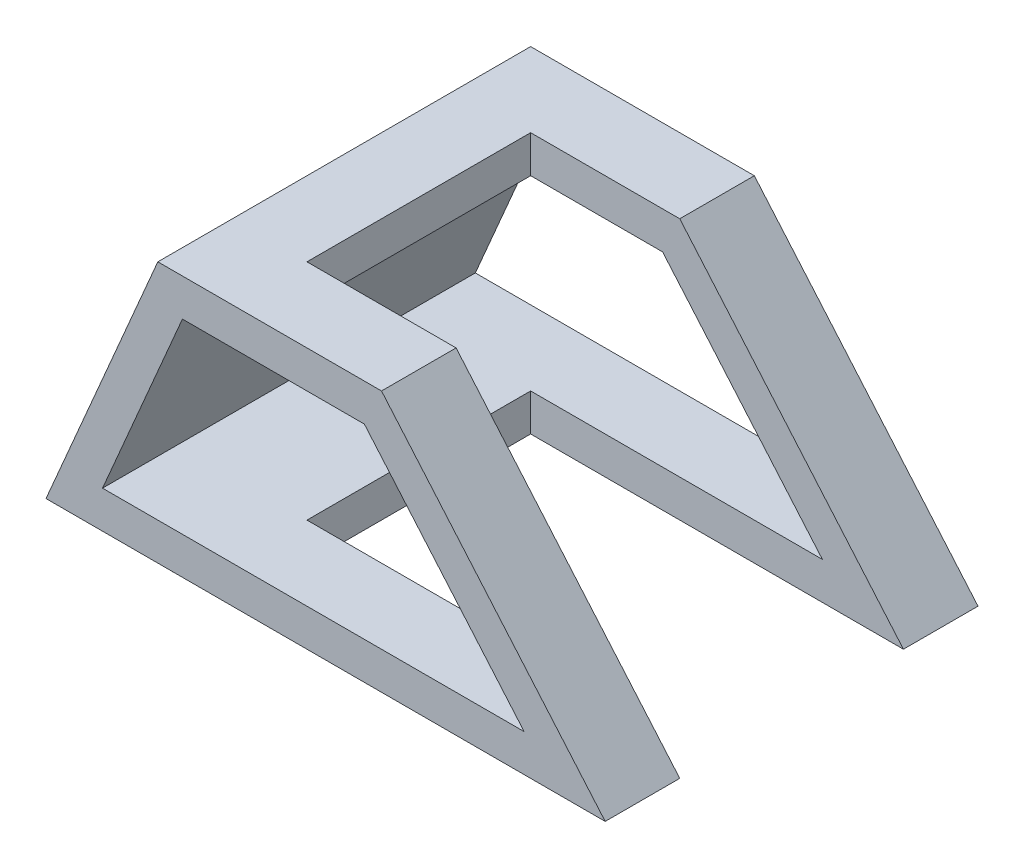
SolidWorks part; units mm, degrees
material "AISI 1020"
ref_plane "Front Plane" through (0, 0, 0) normal (0, 0, 1) x (1, 0, 0)
ref_plane "Top Plane" through (0, 0, 0) normal (0, 1, 0) x (1, 0, 0)
ref_plane "Right Plane" through (0, 0, 0) normal (1, 0, 0) x (0, 0, -1)
sketch "Esquisse1" plane through (0, 0, 0) normal (0, 0, 1) x (1, 0, 0)
  line L0 (0, 0) -> (164.5973, 0) construction
  line L5 (0, 0) -> (150, 0)
  line L6 (150, 0) -> (90, 70)
  line L7 (90, 70) -> (30, 70)
  line L8 (30, 70) -> (0, 0)
  line L9 (36.594, 60) -> (15.1654, 10)
  line L10 (15.1654, 10) -> (128.2578, 10)
  line L11 (128.2578, 10) -> (85.4007, 60)
  line L12 (85.4007, 60) -> (36.594, 60)
  dimension "D1" = 150
  dimension "D2" = 70
  dimension "D3" = 60
  dimension "D4" = 60
  dimension "D5" = 10
extrude "Boss.-Extru.1" add sketch "Esquisse1" against normal blind 100
sketch "Esquisse5" plane through (0, 0, 0) normal (0, -1, 0) x (1, 0, 0)
  line L0 (150, -100) -> (150, 0) construction
  line L1 (150, -20) -> (50, -20)
  line L2 (150, -20) -> (150, -80)
  line L3 (150, -80) -> (50, -80)
  line L4 (50, -20) -> (50, -80)
  line L5 (0, 0) -> (150, 0) construction
  line L6 (0, -100) -> (150, -100) construction
  point P6 (100, -20)
  dimension "D1" = 100
  dimension "D2" = 20
  dimension "D3" = 20
  dimension "D4" = 60
extrude "Enlèv. mat.-Extru.2" cut sketch "Esquisse5" against normal blind 10
sketch "Esquisse6" plane through (86.4706, 74.1176, 0) normal (0.7593, 0.6508, 0) x (0, 0, -1)
  line L0 (80, -84.4479) -> (20, -84.4479) construction
  line L1 (80, -84.4479) -> (20, -84.4479)
  line L2 (80, -84.4479) -> (80, -5.4233)
  line L3 (80, -5.4233) -> (20, -5.4233)
  line L4 (20, -84.4479) -> (20, -5.4233)
  line L5 (100, -5.4233) -> (0, -5.4233) construction
  line L6 (100, -97.6187) -> (100, -5.4233) construction
  line L7 (0, -97.6187) -> (0, -5.4233) construction
  point P8 (80, -44.9356)
  dimension "D1" = 60
  dimension "D2" = 20
  dimension "D3" = 20
extrude "Enlèv. mat.-Extru.3" cut sketch "Esquisse6" against normal blind 10
sketch "Esquisse7" plane through (0, 70, 0) normal (0, 1, 0) x (1, 0, 0)
  line L1 (90, 80) -> (50, 80)
  line L2 (90, 80) -> (90, 20)
  line L3 (90, 20) -> (50, 20)
  line L4 (50, 80) -> (50, 20)
  dimension "D1" = 60
  dimension "D2" = 40
extrude "Enlèv. mat.-Extru.4" cut sketch "Esquisse7" against normal blind 10
